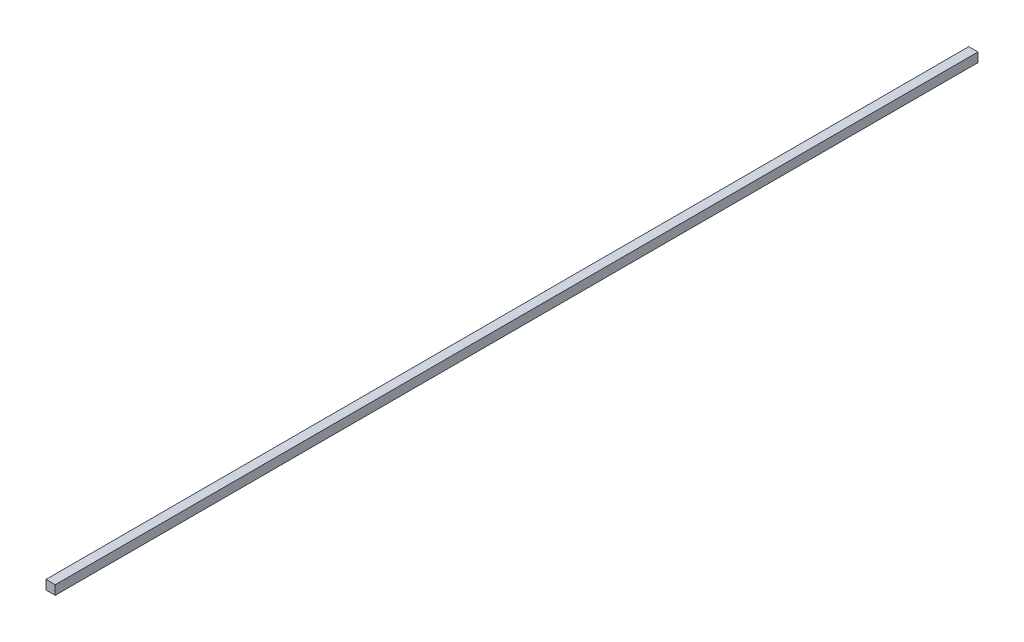
SolidWorks part; units mm, degrees
ref_plane "正面" through (0, 0, 0) normal (0, 0, 1) x (1, 0, 0)
ref_plane "平面" through (0, 0, 0) normal (0, 1, 0) x (1, 0, 0)
ref_plane "右側面" through (0, 0, 0) normal (1, 0, 0) x (0, 0, -1)
sketch "ｽｹｯﾁ1" plane through (0, 0, 0) normal (0, 0, 1) x (1, 0, 0)
  line L1 (0, 0) -> (-10, 0)
  line L2 (0, 0) -> (0, -10)
  line L3 (0, -10) -> (-10, -10)
  line L4 (-10, 0) -> (-10, -10)
extrude "ﾎﾞｽ - 押し出し1" add sketch "ｽｹｯﾁ1" along normal blind 1000
